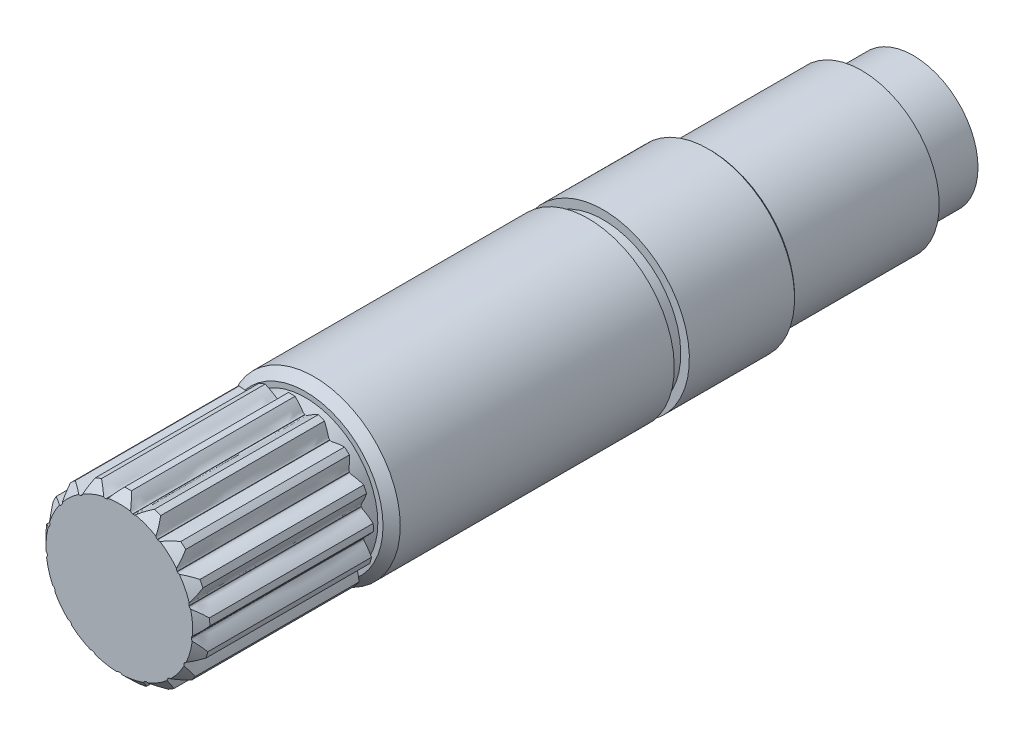
SolidWorks part; units mm, degrees
material "Alloy Steel"
ref_plane "Front Plane" through (0, 0, 0) normal (0, 0, 1) x (1, 0, 0)
ref_plane "Top Plane" through (0, 0, 0) normal (0, 1, 0) x (1, 0, 0)
ref_plane "Right Plane" through (0, 0, 0) normal (1, 0, 0) x (0, 0, -1)
sketch "Sketch12" plane through (0, 0, 0) normal (0, 0, 1) x (1, 0, 0)
  circle A0 centre (0, 0) radius 10
  dimension "D1" = 20
extrude "Shaft" add sketch "Sketch12" along normal mid plane 43
sketch "Sketch13" plane through (0, 0, 21.5) normal (0, 0, 1) x (1, 0, 0)
  circle A0 centre (0, 0) radius 8.3981
  dimension "D1" = 16.7963
extrude "Motor side relief" add sketch "Sketch13" along normal blind 1.587
sketch "Sketch14" plane through (0, 0, -21.5) normal (0, 0, -1) x (-1, 0, 0)
  circle A0 centre (0, 0) radius 8.3981
  dimension "D1" = 16.7963
sketch "Sketch15" plane through (0, 0, 23.087) normal (0, 0, 1) x (1, 0, 0)
  line L38 (4.4402, 7.1283) -> (4.4211, 7.1402)
  line L39 (4.4211, 7.1402) -> (4.4019, 7.1521)
  line L40 (1.5653, 8.251) -> (1.5432, 8.2552)
  line L41 (1.5432, 8.2552) -> (1.521, 8.2593)
  line L42 (-1.521, 8.2593) -> (-1.5432, 8.2552)
  line L43 (-1.5432, 8.2552) -> (-1.5653, 8.251)
  line L44 (-4.4019, 7.1521) -> (-4.4211, 7.1402)
  line L45 (-4.4211, 7.1402) -> (-4.4402, 7.1283)
  line L46 (-6.6882, 5.079) -> (-6.7019, 5.061)
  line L47 (-6.7019, 5.061) -> (-6.7154, 5.043)
  line L48 (-8.0713, 2.32) -> (-8.0776, 2.2983)
  line L49 (-8.0776, 2.2983) -> (-8.0837, 2.2766)
  line L50 (-8.3644, -0.7524) -> (-8.3623, -0.7749)
  line L51 (-8.3623, -0.7749) -> (-8.3602, -0.7973)
  line L52 (-7.5277, -3.7232) -> (-7.5177, -3.7434)
  line L53 (-7.5177, -3.7434) -> (-7.5076, -3.7636)
  line L54 (-5.6744, -6.1911) -> (-5.6578, -6.2063)
  line L55 (-5.6578, -6.2063) -> (-5.6411, -6.2215)
  line L56 (-3.0548, -7.8229) -> (-3.0338, -7.831)
  line L57 (-3.0338, -7.831) -> (-3.0127, -7.8392)
  line L58 (-0.0226, -8.3981) -> (0, -8.3981)
  line L59 (0, -8.3981) -> (0.0226, -8.3981)
  line L60 (3.0127, -7.8392) -> (3.0338, -7.831)
  line L61 (3.0338, -7.831) -> (3.0548, -7.8229)
  line L62 (5.6411, -6.2215) -> (5.6578, -6.2063)
  line L63 (5.6578, -6.2063) -> (5.6744, -6.1911)
  line L64 (7.5076, -3.7636) -> (7.5177, -3.7434)
  line L65 (7.5177, -3.7434) -> (7.5277, -3.7232)
  line L66 (8.3602, -0.7973) -> (8.3623, -0.7749)
  line L67 (8.3623, -0.7749) -> (8.3644, -0.7524)
  line L68 (8.0837, 2.2766) -> (8.0776, 2.2983)
  line L69 (8.0776, 2.2983) -> (8.0713, 2.32)
  line L70 (6.7154, 5.043) -> (6.7019, 5.061)
  line L71 (6.7019, 5.061) -> (6.6882, 5.079)
  arc A19 (6.6912, 6.7683) -> (6.1221, 7.2872) centre (0, 0) ccw
  arc A20 (3.7944, 8.7284) -> (3.0762, 9.0066) centre (0, 0) ccw
  arc A21 (0.3851, 9.5097) -> (-0.3851, 9.5097) centre (0, 0) ccw
  arc A22 (-3.0762, 9.0066) -> (-3.7944, 8.7284) centre (0, 0) ccw
  arc A23 (-6.1221, 7.2872) -> (-6.6912, 6.7683) centre (0, 0) ccw
  arc A24 (-8.3411, 4.5835) -> (-8.6844, 3.8941) centre (0, 0) ccw
  arc A25 (-9.4336, 1.2609) -> (-9.5047, 0.494) centre (0, 0) ccw
  arc A26 (-9.2521, -2.2321) -> (-9.0413, -2.9728) centre (0, 0) ccw
  arc A27 (-7.821, -5.4236) -> (-7.3569, -6.0382) centre (0, 0) ccw
  arc A28 (-5.3336, -7.8826) -> (-4.6788, -8.288) centre (0, 0) ccw
  arc A29 (-2.1259, -9.277) -> (-1.3689, -9.4185) centre (0, 0) ccw
  arc A30 (1.3689, -9.4185) -> (2.1259, -9.277) centre (0, 0) ccw
  arc A31 (4.6788, -8.288) -> (5.3336, -7.8826) centre (0, 0) ccw
  arc A32 (7.3569, -6.0382) -> (7.821, -5.4236) centre (0, 0) ccw
  arc A33 (9.0413, -2.9728) -> (9.2521, -2.2321) centre (0, 0) ccw
  arc A34 (9.5047, 0.494) -> (9.4336, 1.2609) centre (0, 0) ccw
  arc A35 (8.6844, 3.8941) -> (8.3411, 4.5835) centre (0, 0) ccw
  spline S0 degree 3 poles (6.6882, 5.079) (6.6486, 5.1312) (6.6257, 5.1903) (6.6128, 5.3124) (6.6277, 5.3769) (6.657, 5.5736) (6.6884, 5.8472) (6.7084, 6.2901) (6.7009, 6.6058) (6.6912, 6.7683) knots 0 0 0 0 0.125 0.125 0.25 0.25 0.5 0.75 1 1 1 1 weights 1 1 1 1 1 1 1 1 1 1
  spline S1 degree 3 poles (6.1221, 7.2872) (5.9593, 7.2818) (5.6443, 7.2602) (5.2052, 7.1994) (4.9356, 7.1428) (4.7425, 7.0956) (4.6796, 7.0748) (4.5569, 7.0763) (4.4958, 7.0937) (4.4402, 7.1283) knots 0 0 0 0 0.25 0.5 0.75 0.75 0.875 0.875 1 1 1 1 weights 1 1 1 1 1 1 1 1 1 1
  spline S2 degree 3 poles (4.4019, 7.1521) (4.3461, 7.1864) (4.3033, 7.2333) (4.2472, 7.3425) (4.2378, 7.4081) (4.194, 7.602) (4.1245, 7.8685) (3.9832, 8.2887) (3.8621, 8.5804) (3.7944, 8.7284) knots 0 0 0 0 0.125 0.125 0.25 0.25 0.5 0.75 1 1 1 1 weights 1 1 1 1 1 1 1 1 1 1
  spline S3 degree 3 poles (3.0762, 9.0066) (2.9264, 8.9428) (2.6405, 8.8089) (2.253, 8.5935) (2.022, 8.4434) (1.859, 8.3296) (1.8079, 8.2875) (1.6929, 8.2446) (1.6297, 8.2388) (1.5653, 8.251) knots 0 0 0 0 0.25 0.5 0.75 0.75 0.875 0.875 1 1 1 1 weights 1 1 1 1 1 1 1 1 1 1
  spline S4 degree 3 poles (1.521, 8.2593) (1.4566, 8.2711) (1.3997, 8.2994) (1.308, 8.3809) (1.2755, 8.4387) (1.1646, 8.6037) (1.0035, 8.8271) (0.7199, 9.1679) (0.5017, 9.3961) (0.3851, 9.5097) knots 0 0 0 0 0.125 0.125 0.25 0.25 0.5 0.75 1 1 1 1 weights 1 1 1 1 1 1 1 1 1 1
  spline S5 degree 3 poles (-0.3851, 9.5097) (-0.5017, 9.3961) (-0.7199, 9.1679) (-1.0035, 8.8271) (-1.1646, 8.6037) (-1.2755, 8.4387) (-1.308, 8.3809) (-1.3997, 8.2994) (-1.4566, 8.2711) (-1.521, 8.2593) knots 0 0 0 0 0.25 0.5 0.75 0.75 0.875 0.875 1 1 1 1 weights 1 1 1 1 1 1 1 1 1 1
  spline S6 degree 3 poles (-1.5653, 8.251) (-1.6297, 8.2388) (-1.6929, 8.2446) (-1.8079, 8.2875) (-1.859, 8.3296) (-2.022, 8.4434) (-2.253, 8.5935) (-2.6405, 8.8089) (-2.9264, 8.9428) (-3.0762, 9.0066) knots 0 0 0 0 0.125 0.125 0.25 0.25 0.5 0.75 1 1 1 1 weights 1 1 1 1 1 1 1 1 1 1
  spline S7 degree 3 poles (-3.7944, 8.7284) (-3.8621, 8.5804) (-3.9832, 8.2887) (-4.1245, 7.8685) (-4.194, 7.602) (-4.2378, 7.4081) (-4.2472, 7.3425) (-4.3033, 7.2333) (-4.3461, 7.1864) (-4.4019, 7.1521) knots 0 0 0 0 0.25 0.5 0.75 0.75 0.875 0.875 1 1 1 1 weights 1 1 1 1 1 1 1 1 1 1
  spline S8 degree 3 poles (-4.4402, 7.1283) (-4.4958, 7.0937) (-4.5569, 7.0763) (-4.6796, 7.0748) (-4.7425, 7.0956) (-4.9356, 7.1428) (-5.2052, 7.1994) (-5.6443, 7.2602) (-5.9593, 7.2818) (-6.1221, 7.2872) knots 0 0 0 0 0.125 0.125 0.25 0.25 0.5 0.75 1 1 1 1 weights 1 1 1 1 1 1 1 1 1 1
  spline S9 degree 3 poles (-6.6912, 6.7683) (-6.7009, 6.6058) (-6.7084, 6.2901) (-6.6884, 5.8472) (-6.657, 5.5736) (-6.6277, 5.3769) (-6.6128, 5.3124) (-6.6257, 5.1903) (-6.6486, 5.1312) (-6.6882, 5.079) knots 0 0 0 0 0.25 0.5 0.75 0.75 0.875 0.875 1 1 1 1 weights 1 1 1 1 1 1 1 1 1 1
  spline S10 degree 3 poles (-6.7154, 5.043) (-6.7548, 4.9906) (-6.8054, 4.9523) (-6.9193, 4.9066) (-6.9854, 4.9033) (-7.1826, 4.8775) (-7.4544, 4.8329) (-7.8859, 4.7309) (-8.1874, 4.6373) (-8.3411, 4.5835) knots 0 0 0 0 0.125 0.125 0.25 0.25 0.5 0.75 1 1 1 1 weights 1 1 1 1 1 1 1 1 1 1
  spline S11 degree 3 poles (-8.6844, 3.8941) (-8.6347, 3.7391) (-8.5277, 3.442) (-8.349, 3.0363) (-8.2209, 2.7925) (-8.1225, 2.6196) (-8.0853, 2.5648) (-8.0532, 2.4464) (-8.0533, 2.3829) (-8.0713, 2.32) knots 0 0 0 0 0.25 0.5 0.75 0.75 0.875 0.875 1 1 1 1 weights 1 1 1 1 1 1 1 1 1 1
  spline S12 degree 3 poles (-8.0837, 2.2766) (-8.1015, 2.2135) (-8.1348, 2.1595) (-8.2245, 2.0757) (-8.285, 2.0487) (-8.4596, 1.9535) (-8.6968, 1.8137) (-9.0624, 1.5628) (-9.3097, 1.3665) (-9.4336, 1.2609) knots 0 0 0 0 0.125 0.125 0.25 0.25 0.5 0.75 1 1 1 1 weights 1 1 1 1 1 1 1 1 1 1
  spline S13 degree 3 poles (-9.5047, 0.494) (-9.4023, 0.3674) (-9.1952, 0.129) (-8.882, -0.1848) (-8.6745, -0.3658) (-8.5204, -0.4915) (-8.4659, -0.5291) (-8.3931, -0.628) (-8.3702, -0.6872) (-8.3644, -0.7524) knots 0 0 0 0 0.25 0.5 0.75 0.75 0.875 0.875 1 1 1 1 weights 1 1 1 1 1 1 1 1 1 1
  spline S14 degree 3 poles (-8.3602, -0.7973) (-8.354, -0.8625) (-8.3656, -0.925) (-8.419, -1.0355) (-8.4656, -1.0825) (-8.594, -1.2344) (-8.7647, -1.4504) (-9.0149, -1.8164) (-9.1747, -2.0888) (-9.2521, -2.2321) knots 0 0 0 0 0.125 0.125 0.25 0.25 0.5 0.75 1 1 1 1 weights 1 1 1 1 1 1 1 1 1 1
  spline S15 degree 3 poles (-9.0413, -2.9728) (-8.9001, -3.0539) (-8.6209, -3.2014) (-8.2155, -3.3809) (-7.9566, -3.4747) (-7.7675, -3.5362) (-7.7031, -3.5516) (-7.5995, -3.6175) (-7.5568, -3.6645) (-7.5277, -3.7232) knots 0 0 0 0 0.25 0.5 0.75 0.75 0.875 0.875 1 1 1 1 weights 1 1 1 1 1 1 1 1 1 1
  spline S16 degree 3 poles (-7.5076, -3.7636) (-7.4783, -3.8221) (-7.4666, -3.8845) (-7.4764, -4.0068) (-7.5029, -4.0675) (-7.5678, -4.2555) (-7.6489, -4.5187) (-7.75, -4.9504) (-7.8006, -5.262) (-7.821, -5.4236) knots 0 0 0 0 0.125 0.125 0.25 0.25 0.5 0.75 1 1 1 1 weights 1 1 1 1 1 1 1 1 1 1
  spline S17 degree 3 poles (-7.3569, -6.0382) (-7.1959, -6.0628) (-6.8823, -6.0994) (-6.4394, -6.1203) (-6.1641, -6.1143) (-5.9655, -6.1033) (-5.8999, -6.0945) (-5.7795, -6.1185) (-5.7227, -6.1468) (-5.6744, -6.1911) knots 0 0 0 0 0.25 0.5 0.75 0.75 0.875 0.875 1 1 1 1 weights 1 1 1 1 1 1 1 1 1 1
  spline S18 degree 3 poles (-5.6411, -6.2215) (-5.5926, -6.2655) (-5.5591, -6.3194) (-5.5241, -6.437) (-5.5269, -6.5032) (-5.5195, -6.7019) (-5.5001, -6.9766) (-5.4384, -7.4157) (-5.373, -7.7246) (-5.3336, -7.8826) knots 0 0 0 0 0.125 0.125 0.25 0.25 0.5 0.75 1 1 1 1 weights 1 1 1 1 1 1 1 1 1 1
  spline S19 degree 3 poles (-4.6788, -8.288) (-4.5198, -8.2528) (-4.2142, -8.1737) (-3.7936, -8.0332) (-3.5391, -7.9281) (-3.3579, -7.8462) (-3.2999, -7.8142) (-3.179, -7.7931) (-3.1158, -7.799) (-3.0548, -7.8229) knots 0 0 0 0 0.25 0.5 0.75 0.75 0.875 0.875 1 1 1 1 weights 1 1 1 1 1 1 1 1 1 1
  spline S20 degree 3 poles (-3.0127, -7.8392) (-2.9516, -7.8627) (-2.9009, -7.9009) (-2.8257, -7.9979) (-2.8044, -8.0606) (-2.7257, -8.2432) (-2.6084, -8.4924) (-2.3923, -8.8795) (-2.2197, -9.1439) (-2.1259, -9.277) knots 0 0 0 0 0.125 0.125 0.25 0.25 0.5 0.75 1 1 1 1 weights 1 1 1 1 1 1 1 1 1 1
  spline S21 degree 3 poles (-1.3689, -9.4185) (-1.2333, -9.3283) (-0.9769, -9.1441) (-0.6355, -8.8612) (-0.4361, -8.6712) (-0.2968, -8.5294) (-0.2543, -8.4786) (-0.1491, -8.4153) (-0.0881, -8.3979) (-0.0226, -8.3981) knots 0 0 0 0 0.25 0.5 0.75 0.75 0.875 0.875 1 1 1 1 weights 1 1 1 1 1 1 1 1 1 1
  spline S22 degree 3 poles (0.0226, -8.3981) (0.0881, -8.3979) (0.1491, -8.4153) (0.2543, -8.4786) (0.2968, -8.5294) (0.4361, -8.6712) (0.6355, -8.8612) (0.9769, -9.1441) (1.2333, -9.3283) (1.3689, -9.4185) knots 0 0 0 0 0.125 0.125 0.25 0.25 0.5 0.75 1 1 1 1 weights 1 1 1 1 1 1 1 1 1 1
  spline S23 degree 3 poles (2.1259, -9.277) (2.2197, -9.1439) (2.3923, -8.8795) (2.6084, -8.4924) (2.7257, -8.2432) (2.8044, -8.0606) (2.8257, -7.9979) (2.9009, -7.9009) (2.9516, -7.8627) (3.0127, -7.8392) knots 0 0 0 0 0.25 0.5 0.75 0.75 0.875 0.875 1 1 1 1 weights 1 1 1 1 1 1 1 1 1 1
  spline S24 degree 3 poles (3.0548, -7.8229) (3.1158, -7.799) (3.179, -7.7931) (3.2999, -7.8142) (3.3579, -7.8462) (3.5391, -7.9281) (3.7936, -8.0332) (4.2142, -8.1737) (4.5198, -8.2528) (4.6788, -8.288) knots 0 0 0 0 0.125 0.125 0.25 0.25 0.5 0.75 1 1 1 1 weights 1 1 1 1 1 1 1 1 1 1
  spline S25 degree 3 poles (5.3336, -7.8826) (5.373, -7.7246) (5.4384, -7.4157) (5.5001, -6.9766) (5.5195, -6.7019) (5.5269, -6.5032) (5.5241, -6.437) (5.5591, -6.3194) (5.5926, -6.2655) (5.6411, -6.2215) knots 0 0 0 0 0.25 0.5 0.75 0.75 0.875 0.875 1 1 1 1 weights 1 1 1 1 1 1 1 1 1 1
  spline S26 degree 3 poles (5.6744, -6.1911) (5.7227, -6.1468) (5.7795, -6.1185) (5.8999, -6.0945) (5.9655, -6.1033) (6.1641, -6.1143) (6.4394, -6.1203) (6.8823, -6.0994) (7.1959, -6.0628) (7.3569, -6.0382) knots 0 0 0 0 0.125 0.125 0.25 0.25 0.5 0.75 1 1 1 1 weights 1 1 1 1 1 1 1 1 1 1
  spline S27 degree 3 poles (7.821, -5.4236) (7.8006, -5.262) (7.75, -4.9504) (7.6489, -4.5187) (7.5678, -4.2555) (7.5029, -4.0675) (7.4764, -4.0068) (7.4666, -3.8845) (7.4783, -3.8221) (7.5076, -3.7636) knots 0 0 0 0 0.25 0.5 0.75 0.75 0.875 0.875 1 1 1 1 weights 1 1 1 1 1 1 1 1 1 1
  spline S28 degree 3 poles (7.5277, -3.7232) (7.5568, -3.6645) (7.5995, -3.6175) (7.7031, -3.5516) (7.7675, -3.5362) (7.9566, -3.4747) (8.2155, -3.3809) (8.6209, -3.2014) (8.9001, -3.0539) (9.0413, -2.9728) knots 0 0 0 0 0.125 0.125 0.25 0.25 0.5 0.75 1 1 1 1 weights 1 1 1 1 1 1 1 1 1 1
  spline S29 degree 3 poles (9.2521, -2.2321) (9.1747, -2.0888) (9.0149, -1.8164) (8.7647, -1.4504) (8.594, -1.2344) (8.4656, -1.0825) (8.419, -1.0355) (8.3656, -0.925) (8.354, -0.8625) (8.3602, -0.7973) knots 0 0 0 0 0.25 0.5 0.75 0.75 0.875 0.875 1 1 1 1 weights 1 1 1 1 1 1 1 1 1 1
  spline S30 degree 3 poles (8.3644, -0.7524) (8.3702, -0.6872) (8.3931, -0.628) (8.4659, -0.5291) (8.5204, -0.4915) (8.6745, -0.3658) (8.882, -0.1848) (9.1952, 0.129) (9.4023, 0.3674) (9.5047, 0.494) knots 0 0 0 0 0.125 0.125 0.25 0.25 0.5 0.75 1 1 1 1 weights 1 1 1 1 1 1 1 1 1 1
  spline S31 degree 3 poles (9.4336, 1.2609) (9.3097, 1.3665) (9.0624, 1.5628) (8.6968, 1.8137) (8.4596, 1.9535) (8.285, 2.0487) (8.2245, 2.0757) (8.1348, 2.1595) (8.1015, 2.2135) (8.0837, 2.2766) knots 0 0 0 0 0.25 0.5 0.75 0.75 0.875 0.875 1 1 1 1 weights 1 1 1 1 1 1 1 1 1 1
  spline S32 degree 3 poles (8.0713, 2.32) (8.0533, 2.3829) (8.0532, 2.4464) (8.0853, 2.5648) (8.1225, 2.6196) (8.2209, 2.7925) (8.349, 3.0363) (8.5277, 3.442) (8.6347, 3.7391) (8.6844, 3.8941) knots 0 0 0 0 0.125 0.125 0.25 0.25 0.5 0.75 1 1 1 1 weights 1 1 1 1 1 1 1 1 1 1
  spline S33 degree 3 poles (8.3411, 4.5835) (8.1874, 4.6373) (7.8858, 4.731) (7.4544, 4.8329) (7.1826, 4.8775) (6.9854, 4.9033) (6.9193, 4.9066) (6.8054, 4.9523) (6.7548, 4.9906) (6.7154, 5.043) knots 0 0 0 0 0.25 0.5 0.75 0.75 0.875 0.875 1 1 1 1 weights 1 1 1 1 1 1 1 1 1 1
extrude "Motor spline" add sketch "Sketch15" along normal blind 20
chamfer "Chamfer3" distance 1 angle 45 1 edges at (10, 0, 21.5)
sketch "Sketch23" plane through (0, 0, -31.5) normal (-0.948, 0.3182, 0) x (-0.3182, -0.948, 0)
  line L0 (10, 20.2042) -> (9, 20.2042)
  line L1 (9, 20.2042) -> (9, 18.4542)
  line L2 (9, 18.4542) -> (10, 18.4542)
  line L3 (10, 18.4542) -> (10, 20.2042)
  line L4 (10, 10) -> (10, 52) construction
  line L5 (-13.85, 20.2042) -> (13.85, 20.2042) construction
  line L7 (0, 185.3358) -> (0, -121.609) construction
  dimension "D1" = 1.75
  dimension "D2" = 1
revolve "snap ring" cut sketch "Sketch23" angle 360 about L7
sketch "Sketch24" plane through (0, 0, 0) normal (0, 1, 0) x (1, 0, 0)
  line L3 (10, 21.5) -> (10, 25.5)
  line L5 (7.5, 43.5) -> (7.5, 49.5)
  line L6 (7.5, 49.5) -> (0, 49.5)
  line L7 (0, 49.5) -> (0, 21.5)
  line L8 (10, 21.5) -> (-10, 21.5) construction
  line L9 (0, 21.5) -> (10, 21.5)
  line L10 (0, 0) -> (0, 49.7252) construction
  line L12 (7.5, 43.5) -> (9, 43.5)
  line L14 (10, 25.5) -> (9, 25.5)
  line L15 (9, 25.5) -> (9, 43.5)
  dimension "D1" = 15
  dimension "D2" = 22
  dimension "D3" = 4
  dimension "D8" = 6
revolve "Revolve1" add sketch "Sketch24" angle 360 about L10
chamfer "Chamfer4" distance 1 angle 25 2 edges at (9, 0, -43.5) (7.5, 0, -49.5)
chamfer "Chamfer5" distance 0.25 angle 45 1 edges at (10, 0, -25.5)
chamfer "Chamfer6" distance 1 angle 45 17 edges
